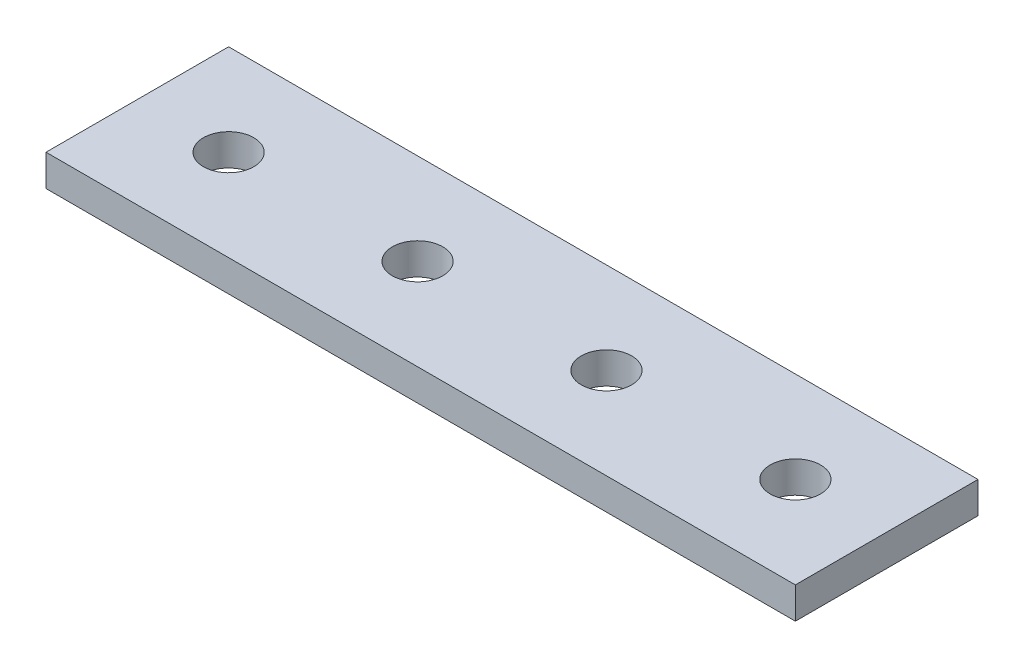
SolidWorks part; units mm, degrees
ref_plane "Front Plane" through (0, 0, 0) normal (0, 0, 1) x (1, 0, 0)
ref_plane "Top Plane" through (0, 0, 0) normal (0, 1, 0) x (1, 0, 0)
ref_plane "Right Plane" through (0, 0, 0) normal (1, 0, 0) x (0, 0, -1)
sketch "Sketch1" plane through (0, 0, 0) normal (0, 1, 0) x (1, 0, 0)
  line L0 (0, 5.8) -> (48, 5.8) construction
  line L1 (0, 0) -> (48, 0)
  line L2 (0, 0) -> (0, 11.6)
  line L3 (0, 11.6) -> (48, 11.6)
  line L4 (48, 0) -> (48, 11.6)
  line L5 (47.8, 11.6) -> (47.8, 0)
  line L6 (0.2, 11.6) -> (0.2, 0)
  point P7 (6, 5.8)
  point P8 (18, 5.8)
  point P9 (30, 5.8)
  point P10 (42, 5.8)
  dimension "D1" = 48
  dimension "D2" = 11.6
  dimension "D3" = 6
  dimension "D4" = 12
  dimension "D5" = 12
  dimension "D6" = 12
  dimension "D7" = 0.2
  dimension "D8" = 0.2
extrude "Boss-Extrude1" add sketch "Sketch1" along normal blind 2 contours L0 L6 L1 L5 | L6 L0 L5 L3
sketch "Sketch2" plane through (0, 2, 0) normal (0, 1, 0) x (1, 0, 0)
  point P0 (42, 5.8)
  point P2 (30, 5.8)
  point P4 (18, 5.8)
  point P6 (6, 5.8)
hole_wizard "M3 Clearance Hole1" positions "Sketch2" profile "Sketch3" hole size "M3" standard "ANSI Metric"
sketch "Sketch3" plane through (42, 2, -5.8) normal (1, 0, 0) x (0, 0, 1)
  line L0 (0, 0) -> (0, 3)
  line L1 (0, 3) -> (1.6, 3)
  line L2 (1.6, 3) -> (1.6, 0)
  line L5 (1.6, 0) -> (0, 0)
  line L10 (0, 3) -> (-1.6, 3) construction
  line L11 (0, -6.35) -> (0, 107.95) construction
  dimension "Hole Dia." = 3.2
  dimension "Hole Depth" = 3
  dimension "Drill Angle" = 180
